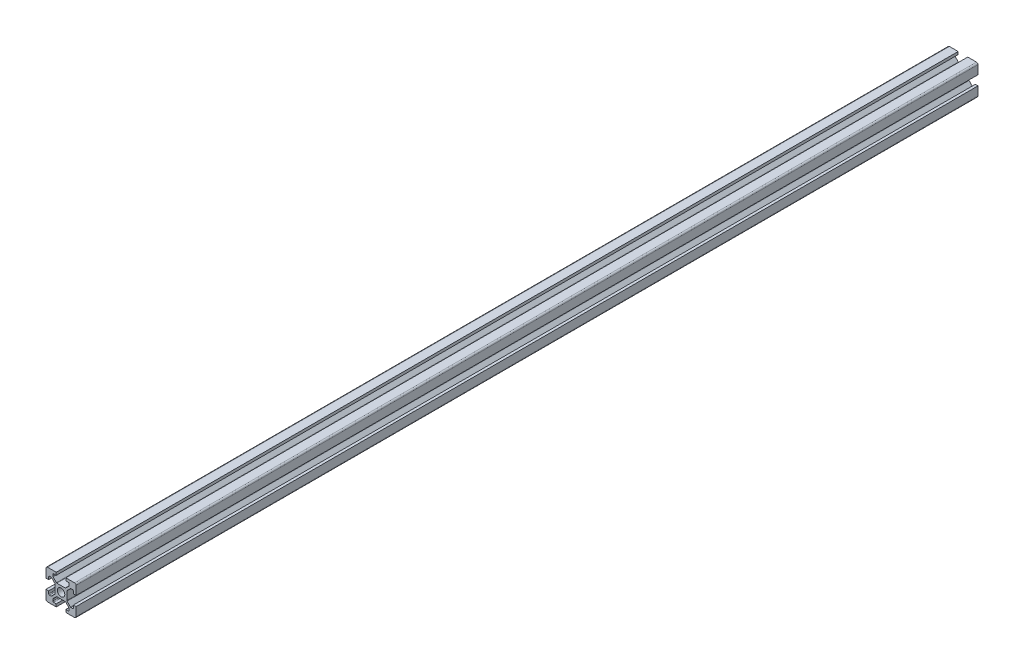
SolidWorks part; units mm, degrees
material "1060 Alloy"
ref_plane "Front Plane" through (0, 0, 0) normal (0, 0, 1) x (1, 0, 0)
ref_plane "Top Plane" through (0, 0, 0) normal (0, 1, 0) x (1, 0, 0)
ref_plane "Right Plane" through (0, 0, 0) normal (1, 0, 0) x (0, 0, -1)
sketch "Sketch1" plane through (0, 0, 0) normal (0, 0, 1) x (1, 0, 0)
  line L0 (20, 0) -> (-8.059, 28.059) construction
  line L1 (0, 0) -> (6.8, 0)
  line L2 (0, 0) -> (0, 6.8)
  line L3 (0, 20) -> (6.8, 20)
  line L4 (20, 0) -> (20, 6.8)
  line L5 (6.8, 20) -> (6.8, 18.2)
  line L6 (20, 20) -> (8.2322, 8.2322) construction
  line L7 (12.95, 6.1) -> (7.05, 6.1)
  line L8 (13.9, 7.05) -> (13.9, 12.95)
  line L9 (12.95, 13.9) -> (7.05, 13.9)
  line L10 (6.1, 7.05) -> (6.1, 12.95)
  line L11 (13.9, 6.1) -> (6.1, 13.9) construction
  line L12 (13.9, 13.9) -> (6.1, 6.1) construction
  line L13 (4.55, 16.4) -> (7.05, 13.9)
  line L14 (13.2, 18.2) -> (13.2, 20)
  line L15 (1.8, 6.8) -> (0, 6.8)
  line L16 (0, 13.2) -> (0, 20)
  line L17 (0, 13.2) -> (1.8, 13.2)
  line L18 (10, 10) -> (10, 13.9) construction
  line L19 (16.4, 4.55) -> (13.9, 7.05)
  line L20 (4.55, 16.4) -> (4.55, 18.2)
  line L21 (4.55, 18.2) -> (6.8, 18.2)
  line L22 (13.2, 18.2) -> (15.45, 18.2)
  line L23 (15.45, 18.2) -> (15.45, 16.4)
  line L24 (15.45, 16.4) -> (12.95, 13.9)
  line L25 (16.4, 4.55) -> (18.2, 4.55)
  line L26 (18.2, 4.55) -> (18.2, 6.8)
  line L27 (20, 6.8) -> (18.2, 6.8)
  line L28 (18.2, 13.2) -> (20, 13.2)
  line L29 (18.2, 13.2) -> (18.2, 15.45)
  line L30 (18.2, 15.45) -> (16.4, 15.45)
  line L31 (16.4, 15.45) -> (13.9, 12.95)
  line L32 (1.8, 4.55) -> (3.6, 4.55)
  line L33 (3.6, 15.45) -> (6.1, 12.95)
  line L34 (3.6, 15.45) -> (1.8, 15.45)
  line L35 (1.8, 15.45) -> (1.8, 13.2)
  line L36 (0, 13.2) -> (1.8, 13.2)
  line L37 (1.8, 6.8) -> (0, 6.8)
  line L38 (3.6, 4.55) -> (6.1, 7.05)
  line L39 (1.8, 6.8) -> (1.8, 4.55)
  line L40 (15.45, 3.6) -> (12.95, 6.1)
  line L41 (4.55, 3.6) -> (7.05, 6.1)
  line L42 (4.55, 1.8) -> (4.55, 3.6)
  line L43 (6.8, 1.8) -> (4.55, 1.8)
  line L44 (6.8, 1.8) -> (6.8, 0)
  line L45 (15.45, 3.6) -> (15.45, 1.8)
  line L46 (15.45, 1.8) -> (13.2, 1.8)
  line L47 (13.2, 0) -> (13.2, 1.8)
  line L48 (13.2, 20) -> (20, 20)
  line L49 (20, 13.2) -> (20, 20)
  line L50 (13.2, 0) -> (20, 0)
  line L51 (6.1, 6.1) -> (-5.5045, -5.5045) construction
  circle A0 centre (10, 10) radius 2.5
  point P25 (10, 16.4)
  point P39 (13.2, 19.1)
  point P46 (0.9, 6.8)
  dimension "D3" = 5
  dimension "D2" = 20
  dimension "D4" = 7.8
  dimension "D5" = 7.8
  dimension "D6" = 6.8
  dimension "D7" = 6.8
  dimension "D8" = 1.8
  dimension "D9" = 10.9
  dimension "D10" = 1.8
  dimension "D11" = 10.9
  dimension "D12" = 20
extrude "Boss-Extrude1" add sketch "Sketch1" along normal blind 300 contours L47 L50 L4 L27 L26 L25 L19 L8 L31 L30 L29 L28 L49 L48 L14 L22 L23 L24 L9 L13 L20 L21 L5 L3 L16 L17 L35 L34 L33 L10 L38 L32 L39 L15 L2 L1 L44 L43 L42 L41 L7 L40 L45 L46 A0
fillet "Fillet1" radius 1 4 edges at (20, 20, 150) (20, 0, 150) (0, 0, 150) (0, 20, 150)
fillet "Fillet2" radius 0.5 6 edges at (4.55, 18.2, 150) (4.55, 16.4, 150) (7.05, 13.9, 150) (15.45, 18.2, 150) (15.45, 16.4, 150) (12.95, 13.9, 150)
fillet "Fillet3" radius 0.5 6 edges at (18.2, 15.45, 150) (16.4, 15.45, 150) (13.9, 12.95, 150) (18.2, 4.55, 150) (13.9, 7.05, 150) (16.4, 4.55, 150)
fillet "Fillet4" radius 0.5 6 edges at (1.8, 15.45, 150) (3.6, 15.45, 150) (6.1, 12.95, 150) (3.6, 4.55, 150) (1.8, 4.55, 150) (6.1, 7.05, 150)
fillet "Fillet5" radius 0.5 6 edges at (7.05, 6.1, 150) (4.55, 3.6, 150) (4.55, 1.8, 150) (15.45, 1.8, 150) (15.45, 3.6, 150) (12.95, 6.1, 150)
mirror "Mirror1" about plane through (0, 0, 300) normal (0, 0, 1) of bodies 101
